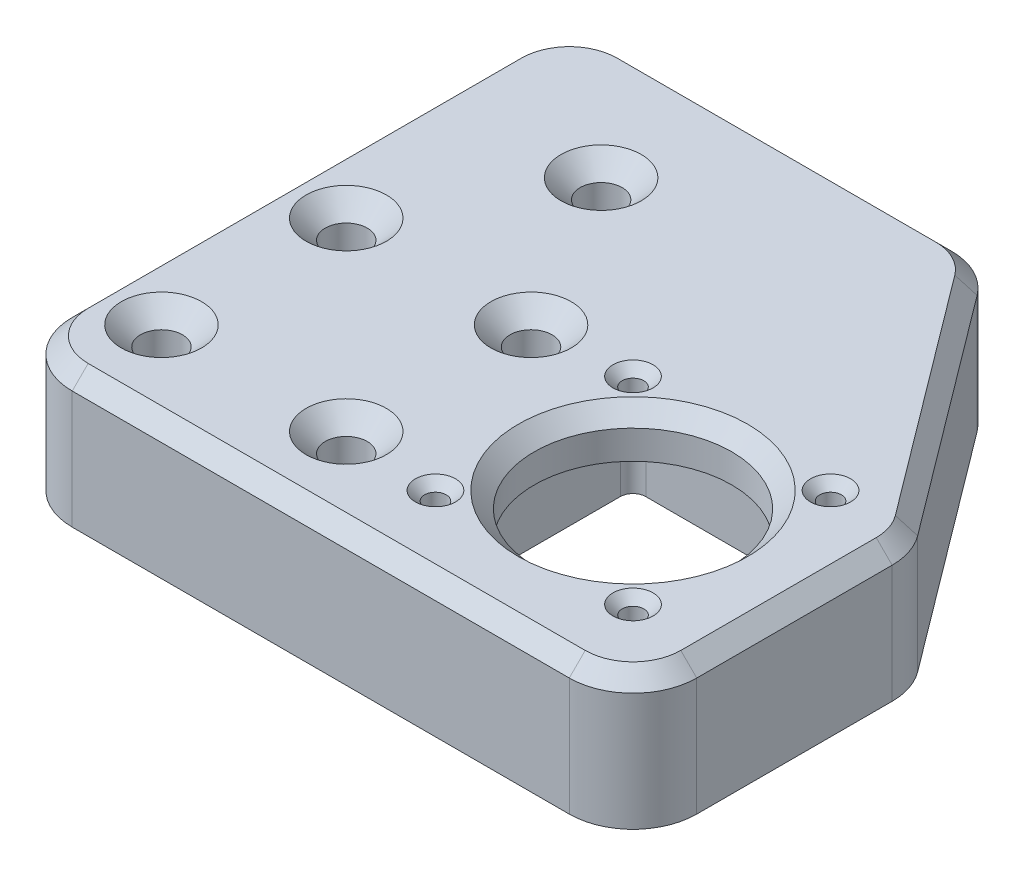
SolidWorks part; units mm, degrees
material "3.1355 (EN-AW 2024)"
ref_plane "Front" through (0, 0, 0) normal (0, 0, 1) x (1, 0, 0)
ref_plane "Top" through (0, 0, 0) normal (0, 1, 0) x (1, 0, 0)
ref_plane "Right" through (0, 0, 0) normal (1, 0, 0) x (0, 0, -1)
sketch "Эскиз1" plane through (0, 0, 0) normal (0, 1, 0) x (1, 0, 0)
  line L1 (-40, 40) -> (40, 40)
  line L2 (-40, 40) -> (-40, -40)
  line L3 (-40, -40) -> (40, -40)
  line L4 (40, 40) -> (40, -40)
  line L5 (-40, 40) -> (40, -40) construction
  line L6 (-40, -40) -> (40, 40) construction
  point P0 (0, 0)
  dimension "D1" = 80
extrude "База" add sketch "Эскиз1" along normal blind 21
sketch "Эскиз9" plane through (0, 21, 0) normal (0, 1, 0) x (1, 0, 0)
  line L0 (40, 40) -> (93, 40)
  line L1 (93, 40) -> (93, -48)
  line L2 (93, -48) -> (-40, -48)
  line L3 (-40, -48) -> (-40, -40)
  line L4 (-40, -40) -> (40, -40)
  line L5 (40, -40) -> (40, 40)
  dimension "D1" = 53
  dimension "D2" = 8
extrude "База-2" add sketch "Эскиз9" against normal up to surface (21 mm away) up to face at (0, 0, 0)
hole_wizard "Крепление-M6" positions "Эскиз6" profile "Эскиз8" countersink size "M6" standard "DIN" end condition through all
sketch "Эскиз6" plane through (0, 21, 0) normal (0, 1, 0) x (1, 0, 0)
  line L0 (0, 0) -> (-20, 0) construction
  line L1 (-20, 0) -> (-40, 0) construction
  line L2 (-40, 40) -> (-40, -48) construction
  line L5 (0, 0) -> (20, 0) construction
  line L6 (20, 0) -> (40, 0) construction
  line L10 (0, 0) -> (0, -20) construction
  line L11 (0, -20) -> (0, -40) construction
  line L15 (0, 0) -> (0, 20) construction
  line L16 (0, 20) -> (0, 40) construction
  line L20 (5.5, -34.5) -> (5.5, -20) construction
  line L21 (5.5, -20) -> (5.5, -5.5) construction
  line L26 (5.5, -34.5) -> (20, -34.5) construction
  line L27 (20, -34.5) -> (34.5, -34.5) construction
  point P0 (-20, -20)
  point P2 (20, 20)
  point P41 (5.5, -5.5)
  point P43 (34.5, -5.5)
  point P45 (34.5, -34.5)
  point P47 (5.5, -34.5)
  dimension "D1" = 29
  dimension "D2" = 20
sketch "Эскиз8" plane through (-20, 21, 20) normal (1, 0, 0) x (0, 0, 1)
  line L0 (0, 0) -> (0, 21)
  line L1 (0, 21) -> (3.3, 21)
  line L2 (3.3, 21) -> (3.3, 3)
  line L3 (3.3, 3) -> (6.3, 0)
  line L5 (6.3, 0) -> (0, 0)
  line L6 (-3.3, 3) -> (-6.3, 0) construction
  line L11 (0, -6.35) -> (0, 107.95) construction
  dimension "Диаметр сквозного отверстия" = 6.6
  dimension "Глубина сквозного отверстия" = 21
  dimension "Диаметр передней зенковки" = 12.6
  dimension "Угол передней зенковки" = 90
sketch "Эскиз10" plane through (0, 0, 0) normal (0, -1, 0) x (1, 0, 0)
  line L1 (0, 0) -> (40, 0)
  line L2 (0, 0) -> (0, 40)
  line L3 (0, 40) -> (40, 40)
  line L4 (40, 0) -> (40, 40)
  dimension "D1" = 40
extrude "Профиль-40" cut sketch "Эскиз10" against normal blind 11.5
sketch "Эскиз11" plane through (0, 0, 0) normal (0, -1, 0) x (1, 0, 0)
  line L0 (40, 0) -> (40, 40) construction
  line L1 (43.85, 41.15) -> (86.15, 41.15)
  line L2 (43.85, 41.15) -> (43.85, -1.15)
  line L3 (43.85, -1.15) -> (86.15, -1.15)
  line L4 (86.15, 41.15) -> (86.15, -1.15)
  line L5 (43.85, 41.15) -> (86.15, -1.15) construction
  line L6 (43.85, -1.15) -> (86.15, 41.15) construction
  point P0 (65, 20)
  point P7 (40, 20)
  dimension "D1" = 42.3
  dimension "D2" = 65
extrude "Nema17" cut sketch "Эскиз11" against normal blind 14
hole_wizard "Nema17-M3" positions "Эскиз12" profile "Эскиз13" countersink size "M3" standard "DIN" end condition through all
sketch "Эскиз12" plane through (0, 21, 0) normal (0, -1, 0) x (-1, 0, 0)
  line L0 (-80.5, -4.5) -> (-65, -4.5) construction
  line L1 (-65, -4.5) -> (-49.5, -4.5) construction
  line L2 (-49.5, -4.5) -> (-49.5, -20) construction
  line L3 (-49.5, -20) -> (-49.5, -35.5) construction
  line L7 (-43.85, 1.15) -> (-86.15, 1.15) construction
  line L8 (-43.85, -41.15) -> (-43.85, 1.15) construction
  point P0 (-49.5, -35.5)
  point P2 (-80.5, -35.5)
  point P4 (-80.5, -4.5)
  point P6 (-49.5, -4.5)
  point P28 (-65, 1.15)
  point P31 (-43.85, -20)
  dimension "D1" = 31
sketch "Эскиз13" plane through (49.5, 21, 35.5) normal (1, 0, 0) x (0, 0, 1)
  line L0 (0, 0) -> (0, 21)
  line L1 (0, 21) -> (1.7, 21)
  line L2 (1.7, 21) -> (1.7, 1.45)
  line L3 (1.7, 1.45) -> (3.15, 0)
  line L5 (3.15, 0) -> (0, 0)
  line L6 (-1.7, 1.45) -> (-3.15, 0) construction
  line L11 (0, -6.35) -> (0, 107.95) construction
  dimension "Диаметр сквозного отверстия" = 3.4
  dimension "Глубина сквозного отверстия" = 21
  dimension "Диаметр передней зенковки" = 6.3
  dimension "Угол передней зенковки" = 90
fillet "Скругление1" radius 2 8 edges at (0, 5.75, 40) (40, 5.75, 40) (40, 5.75, 0) (0, 5.75, 0) (86.15, 7, -1.15) (86.15, 7, 41.15) (43.85, 7, 41.15) (43.85, 7, -1.15)
sketch "Эскиз14" plane through (0, 14, 0) normal (0, -1, 0) x (1, 0, 0)
  line L0 (43.85, 39.15) -> (43.85, 0.85) construction
  line L1 (84.15, 41.15) -> (45.85, 41.15) construction
  circle A0 centre (65, 20) radius 15.5
  point P4 (43.85, 20)
  point P7 (65, 41.15)
  dimension "D1" = 31
extrude "Вырез-Nema23" cut sketch "Эскиз14" against normal through all
sketch "Эскиз2" plane through (0, 21, 0) normal (0, 1, 0) x (1, 0, 0)
  line L1 (93, 40) -> (-40, 40) construction
  line L3 (-40, -48) -> (-5, -48)
  line L10 (-40, -48) -> (-40, 40)
  line L11 (-40, 40) -> (-5, 40)
  line L12 (-5, -48) -> (-5, 40)
  line L13 (0, -38) -> (0, -2) construction
  dimension "D1" = 5
extrude "Срез" cut sketch "Эскиз2" against normal through all
sketch "Эскиз15" plane through (0, 21, 0) normal (0, 1, 0) x (1, 0, 0)
  line L0 (60, 40) -> (93, -4)
  line L2 (93, -48) -> (93, 40) construction
  line L3 (93, -4) -> (93, 40)
  line L4 (93, 40) -> (60, 40)
  dimension "D1" = 60
extrude "Вырез-Вытянуть1" cut sketch "Эскиз15" against normal through all
fillet "Скругление2" radius 10 5 edges at (-5, 10.5, -40) (93, 10.5, 48) (-5, 10.5, 48) (93, 10.5, 4) (60, 10.5, -40)
chamfer "Фаска1" distance 2.5 angle 45 11 edges at (65, 21, 4.5) (44, 21, 48) (90.0711, 21, 45.0711) (93, 21, 22.6667) (30, 21, -40) (-2.0711, 21, -37.0711) (-5, 21, 4) (-2.0711, 21, 45.0711) (77, 21, -17.3333) (92.4868, 21, 4.1711) (59.4721, 21, -38.9443)
